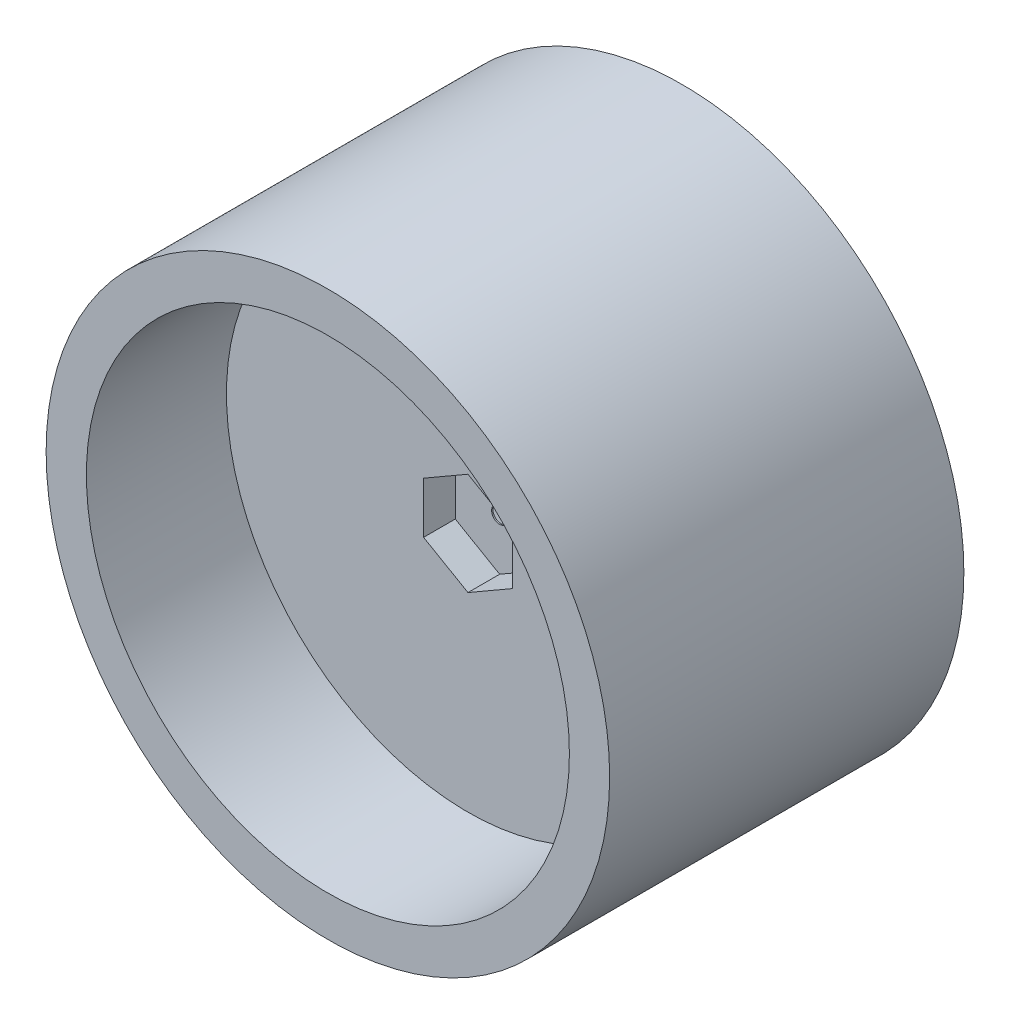
SolidWorks part; units mm, degrees
ref_plane "Front Plane" through (0, 0, 0) normal (0, 0, 1) x (1, 0, 0)
ref_plane "Top Plane" through (0, 0, 0) normal (0, 1, 0) x (1, 0, 0)
ref_plane "Right Plane" through (0, 0, 0) normal (1, 0, 0) x (0, 0, -1)
sketch "Sketch1" plane through (0, 0, 0) normal (0, 0, 1) x (1, 0, 0)
  circle A0 centre (0, 0) radius 44.45
  dimension "D1" = 88.9
extrude "Boss-Extrude1" add sketch "Sketch1" along normal blind 55.88
sketch "Sketch2" plane through (0, 0, 55.88) normal (0, 0, 1) x (1, 0, 0)
  circle A0 centre (0, 0) radius 38.1
  dimension "D1" = 76.2
extrude "Cut-Extrude1" cut sketch "Sketch2" against normal blind 22.098
sketch "Sketch3" plane through (0, 0, 0) normal (0, 0, -1) x (-1, 0, 0)
  circle A0 centre (0, 0) radius 38.1
  dimension "D1" = 76.2
extrude "Cut-Extrude2" cut sketch "Sketch3" against normal blind 28.575
sketch "Sketch4" plane through (0, 0, 33.782) normal (0, 0, 1) x (1, 0, 0)
  circle A0 centre (0, 0) radius 1.27
  dimension "D1" = 2.54
extrude "Cut-Extrude3" cut sketch "Sketch4" against normal through all
sketch "Sketch5" plane through (0, 0, 33.782) normal (0, 0, 1) x (1, 0, 0)
  line L1 (0, 8.0829) -> (-7, 4.0415)
  line L2 (-7, 4.0415) -> (-7, -4.0415)
  line L3 (-7, -4.0415) -> (0, -8.0829)
  line L4 (0, -8.0829) -> (7, -4.0415)
  line L5 (7, -4.0415) -> (7, 4.0415)
  line L6 (7, 4.0415) -> (0, 8.0829)
  circle A0 centre (0, 0) radius 7 construction
extrude "Cut-Extrude4" cut sketch "Sketch5" against normal blind 5
